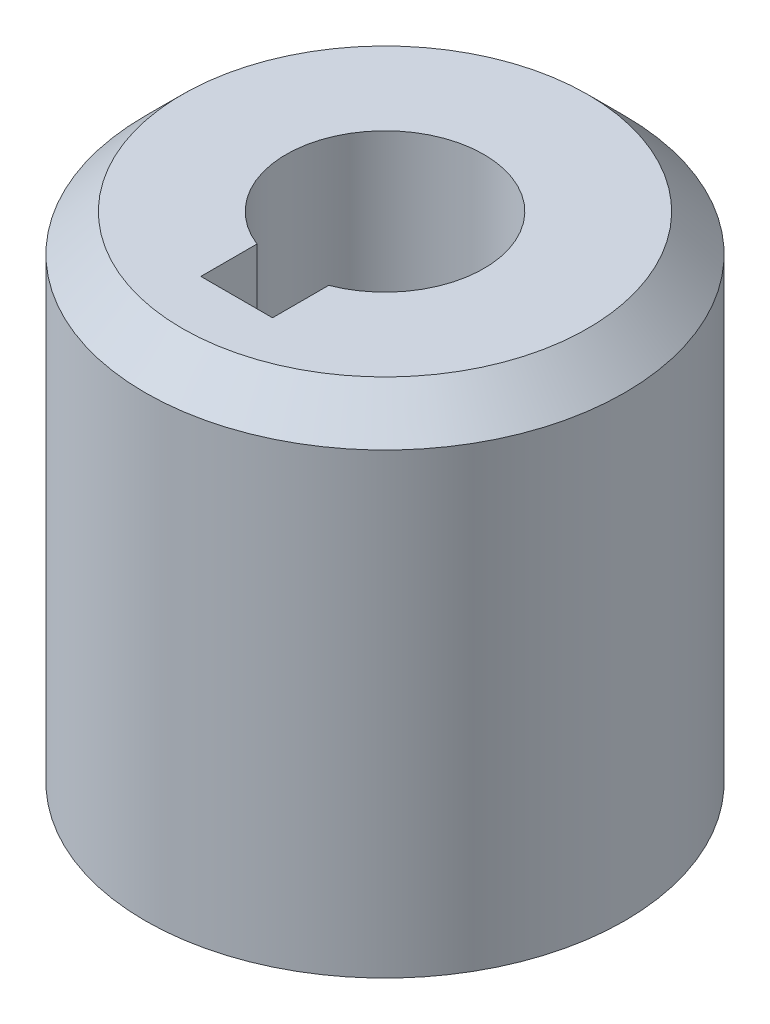
SolidWorks part; units mm, degrees
ref_plane "Front Plane" through (0, 0, 0) normal (0, 0, 1) x (1, 0, 0)
ref_plane "Top Plane" through (0, 0, 0) normal (0, 1, 0) x (1, 0, 0)
ref_plane "Right Plane" through (0, 0, 0) normal (1, 0, 0) x (0, 0, -1)
sketch "Sketch1" plane through (0, 0, 0) normal (0, 1, 0) x (1, 0, 0)
  line L1 (-1.45, -6) -> (1.45, -6)
  line L5 (0, -6) -> (0, -4) construction
  line L8 (-1.45, -6) -> (-1.45, -3.7279)
  line L10 (1.45, -6) -> (1.45, -3.7279)
  circle A0 centre (0, 0) radius 9.7
  arc A1 (1.45, -3.7279) -> (-1.45, -3.7279) centre (0, 0) ccw
  circle A2 centre (0, 0) radius 4 construction
  dimension "D1" = 19.4
  dimension "D2" = 8
  dimension "D3" = 6
  dimension "D4" = 2.9
extrude "Boss-Extrude1" add sketch "Sketch1" along normal blind 20
chamfer "Chamfer1" distance 1.5 angle 45 1 edges at (0, 20, 9.7)
